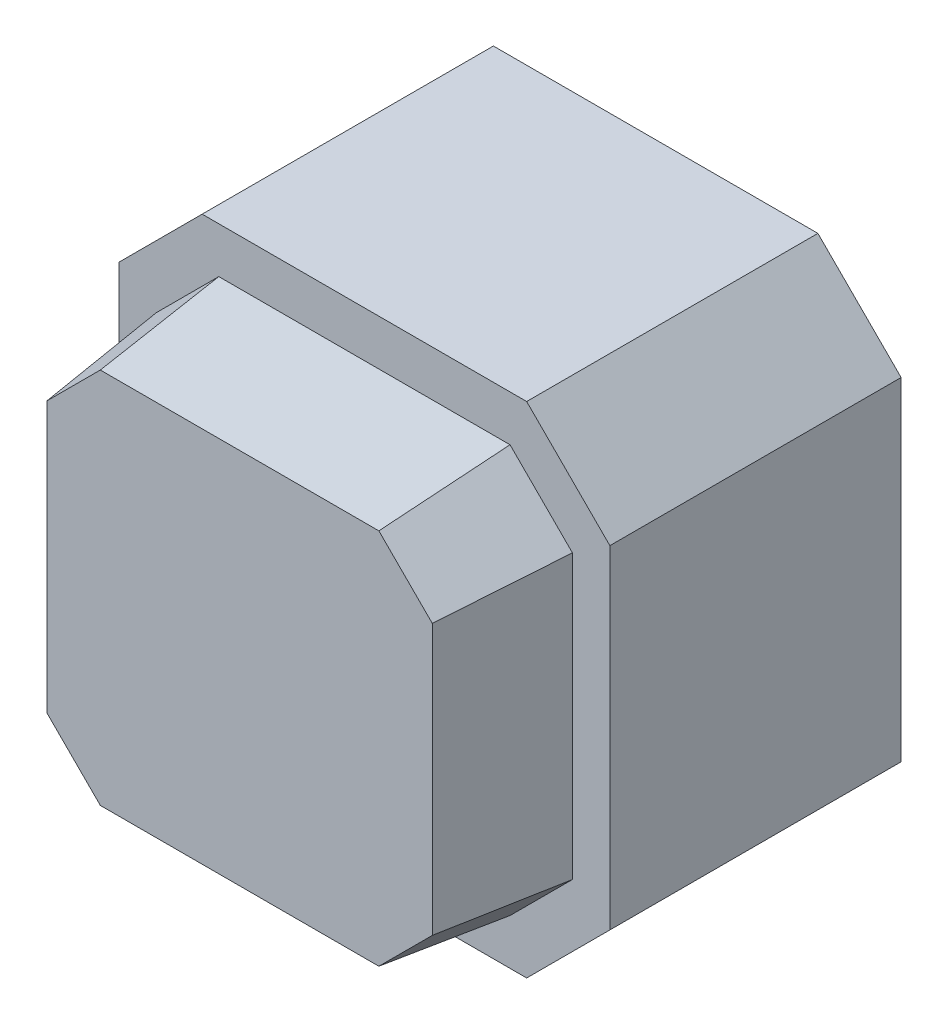
SolidWorks part; units mm, degrees
ref_plane "Front Plane" through (0, 0, 0) normal (0, 0, 1) x (1, 0, 0)
ref_plane "Top Plane" through (0, 0, 0) normal (0, 1, 0) x (1, 0, 0)
ref_plane "Right Plane" through (0, 0, 0) normal (1, 0, 0) x (0, 0, -1)
sketch "Sketch1" plane through (0, 0, 0) normal (0, 0, 1) x (1, 0, 0)
  line L0 (-2.95, 2) -> (-1.95, 3)
  line L1 (-1.95, -3) -> (1.95, -3)
  line L2 (-2.95, -2) -> (-2.95, 2)
  line L3 (-1.95, 3) -> (1.95, 3)
  line L4 (2.95, -2) -> (2.95, 2)
  line L5 (-2.95, -3) -> (2.95, 3) construction
  line L6 (-2.95, 3) -> (2.95, -3) construction
  line L7 (1.95, 3) -> (2.95, 2)
  line L8 (1.95, -3) -> (2.95, -2)
  line L9 (-1.95, -3) -> (-2.95, -2)
  point P0 (0, 0)
  dimension "D1" = 5.9
  dimension "D2" = 6
extrude "Boss-Extrude1" add sketch "Sketch1" along normal blind 3.5
sketch "Sketch2" plane through (0, 0, 3.5) normal (0, 0, 1) x (1, 0, 0)
  line L0 (-2.5, 1.7) -> (-1.75, 2.45)
  line L1 (-1.75, -2.45) -> (1.75, -2.45)
  line L2 (-2.5, -1.7) -> (-2.5, 1.7)
  line L3 (-1.75, 2.45) -> (1.75, 2.45)
  line L4 (2.5, -1.7) -> (2.5, 1.7)
  line L5 (-2.5, -2.45) -> (2.5, 2.45) construction
  line L6 (-2.5, 2.45) -> (2.5, -2.45) construction
  line L7 (1.75, 2.45) -> (2.5, 1.7)
  line L8 (1.75, -2.45) -> (2.5, -1.7)
  line L9 (-2.5, -1.7) -> (-1.75, -2.45)
  point P0 (0, 0)
  dimension "D1" = 5
  dimension "D2" = 4.9
extrude "Boss-Extrude2" add sketch "Sketch2" along normal blind 1.5 draft 7
